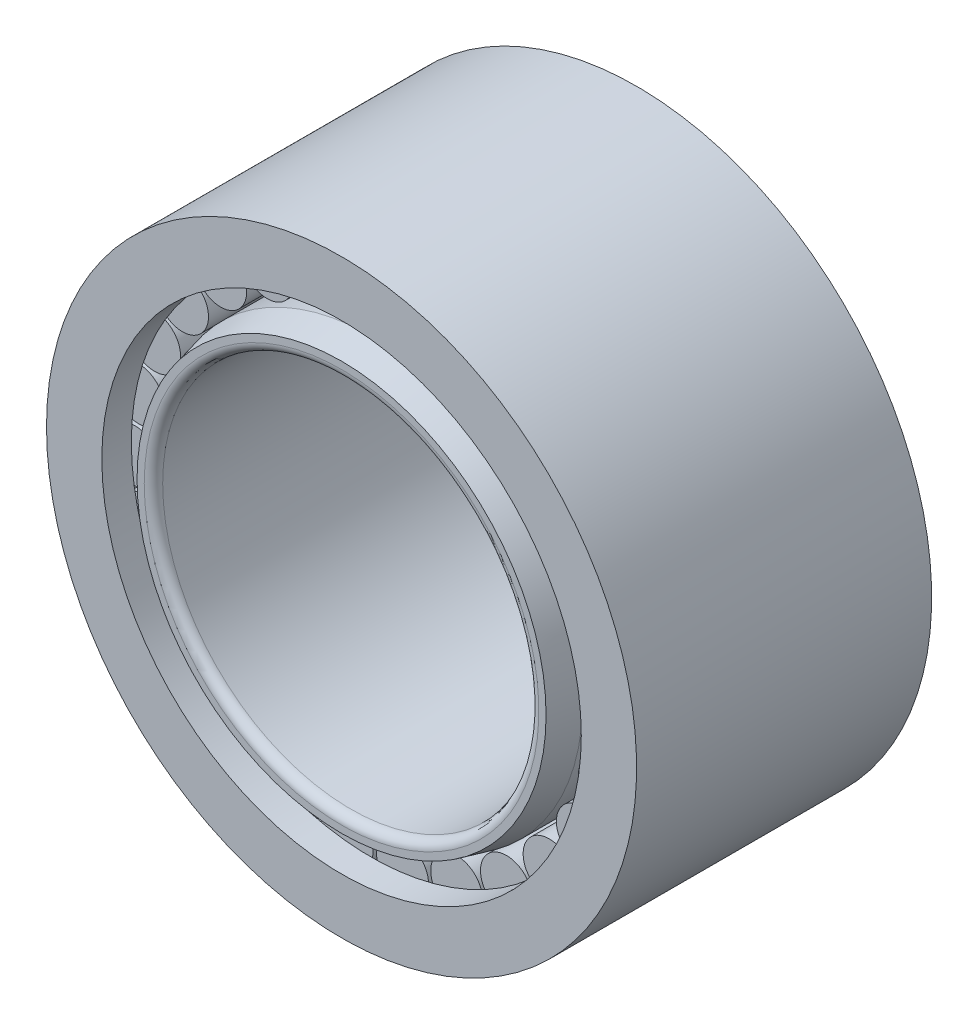
SolidWorks part; units mm, degrees
ref_plane "Front Plane" through (0, 0, 0) normal (0, 0, 1) x (1, 0, 0)
ref_plane "Top Plane" through (0, 0, 0) normal (0, 1, 0) x (1, 0, 0)
ref_plane "Right Plane" through (0, 0, 0) normal (1, 0, 0) x (0, 0, -1)
sketch "Sketch1" plane through (0, 0, 0) normal (1, 0, 0) x (0, 0, -1)
  line L0 (-8, 13) -> (-8, 16)
  line L1 (-8, 16) -> (8, 16)
  line L2 (8, 16) -> (8, 13)
  line L3 (8, 13) -> (6.4, 13)
  line L4 (6.4, 13) -> (6.4, 14.53)
  line L5 (6.4, 14.53) -> (-6.4, 14.53)
  line L6 (-6.4, 14.53) -> (-6.4, 13)
  line L7 (-6.4, 13) -> (-8, 13)
  point P7 (0, 14.53)
  dimension "D1" = 16
  dimension "D2" = 14.53
  dimension "D3" = 13
  dimension "D4" = 1.6
  dimension "D5" = 16
ref_axis "Axis1" through (0, 0, -22) along (0, 0, 1)
revolve "Revolve1" add sketch "Sketch1" angle 360 about axis through (0, 0, -22) along (0, 0, 1)
sketch "Sketch2" plane through (0, 0, 0) normal (1, 0, 0) x (0, 0, -1)
  line L0 (7.5, 10.2) -> (-7.5, 10.2)
  line L1 (-8, 11.09) -> (-6.4, 11.47)
  line L2 (-6.4, 11.47) -> (6.4, 11.47)
  line L3 (6.4, 11.47) -> (8, 11.09)
  line L4 (8, 11.09) -> (8, 10.7)
  line L5 (-8, 11.09) -> (-8, 10.7)
  line L6 (22, 0) -> (-22, 0) construction
  arc A0 (7.5, 10.2) -> (8, 10.7) centre (7.5, 10.7) ccw
  arc A1 (-7.5, 10.2) -> (-8, 10.7) centre (-7.5, 10.7) cw
  point P13 (0, 10.2)
  point P15 (0, 11.47)
  dimension "D1" = 0.5
  dimension "D4" = 10.2
  dimension "D2" = 16
  dimension "D3" = 11.47
  dimension "D5" = 12.8
  dimension "D6" = 11.09
revolve "Revolve2" add sketch "Sketch2" angle 360 about axis through (0, 0, -22) along (0, 0, 1)
sketch "Sketch3" plane through (0, 0, 0) normal (1, 0, 0) x (0, 0, -1)
  line L0 (-6.2, 13) -> (-6.2, 14.41)
  line L1 (-6.2, 14.41) -> (6.2, 14.41)
  line L2 (6.2, 14.41) -> (6.2, 13)
  line L3 (6.2, 13) -> (-6.2, 13)
  line L4 (22, 0) -> (-22, 0) construction
  point P4 (0, 13)
  dimension "D1" = 12.4
  dimension "D2" = 1.41
  dimension "D3" = 13
revolve "Revolve3" add sketch "Sketch3" angle 360 about L3
pattern_circular "CirPattern1" count 27 over 360 about axis through (0, 0, 0) along (0, 0, 1) of bodies 103
